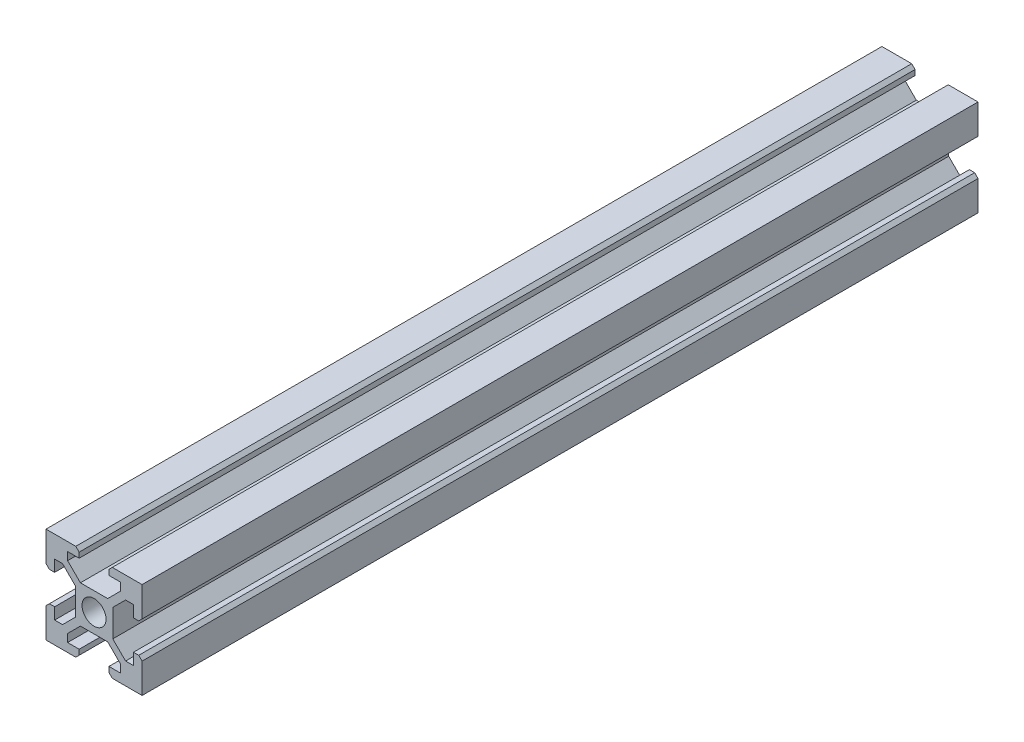
SolidWorks part; units mm, degrees
material "1060 Alloy"
ref_plane "Front Plane" through (0, 0, 0) normal (0, 0, 1) x (1, 0, 0)
ref_plane "Top Plane" through (0, 0, 0) normal (0, 1, 0) x (1, 0, 0)
ref_plane "Right Plane" through (0, 0, 0) normal (1, 0, 0) x (0, 0, -1)
sketch "Sketch1" plane through (0, 0, 0) normal (0, 0, 1) x (1, 0, 0)
  line L0 (3.9, -2.8393) -> (6.5607, -5.5)
  line L1 (-10, 10) -> (10, 10) construction
  line L2 (-10, 10) -> (-10, -10) construction
  line L3 (-10, -10) -> (10, -10) construction
  line L4 (10, 10) -> (10, -10) construction
  line L5 (-10, 10) -> (10, -10) construction
  line L6 (-10, -10) -> (10, 10) construction
  line L7 (-3.9, -3.9) -> (3.9, -3.9) construction
  line L8 (-3.9, -3.9) -> (-3.9, 3.9) construction
  line L9 (-3.9, 3.9) -> (3.9, 3.9) construction
  line L10 (3.9, -3.9) -> (3.9, 3.9) construction
  line L11 (-3.9, -3.9) -> (3.9, 3.9) construction
  line L12 (-3.9, 3.9) -> (3.9, -3.9) construction
  line L13 (-10, 10) -> (-5.5, 10) construction
  line L14 (-10, 10) -> (-10, 5.5) construction
  line L15 (-10, 5.5) -> (-5.5, 5.5) construction
  line L16 (-5.5, 10) -> (-5.5, 5.5) construction
  line L17 (10, 10) -> (5.5, 10) construction
  line L18 (10, 10) -> (10, 5.5) construction
  line L19 (10, 5.5) -> (5.5, 5.5) construction
  line L20 (5.5, 10) -> (5.5, 5.5) construction
  line L21 (-10, -10) -> (-5.5, -10) construction
  line L22 (-10, -10) -> (-10, -5.5) construction
  line L23 (-10, -5.5) -> (-5.5, -5.5) construction
  line L24 (-5.5, -10) -> (-5.5, -5.5) construction
  line L25 (10, -10) -> (5.5, -10) construction
  line L26 (10, -10) -> (10, -5.5) construction
  line L27 (10, -5.5) -> (5.5, -5.5) construction
  line L28 (5.5, -10) -> (5.5, -5.5) construction
  line L29 (2.8393, -3.9) -> (5.5, -6.5607)
  line L30 (-5.5, 6.5607) -> (-2.8393, 3.9)
  line L31 (-6.5607, 5.5) -> (-3.9, 2.8393)
  line L32 (5.5, 6.5607) -> (2.8393, 3.9)
  line L33 (6.5607, 5.5) -> (3.9, 2.8393)
  line L34 (-6.5607, -5.5) -> (-3.9, -2.8393)
  line L35 (-5.5, -6.5607) -> (-2.8393, -3.9)
  line L36 (-2.8393, 3.9) -> (2.8393, 3.9)
  line L37 (-3.9, 2.8393) -> (-3.9, -2.8393)
  line L38 (-2.8393, -3.9) -> (2.8393, -3.9)
  line L39 (3.9, -2.8393) -> (3.9, 2.8393)
  line L40 (5.5, 6.5607) -> (5.5, 8.2007)
  line L41 (5.5, 8.2007) -> (3.1, 8.2007)
  line L42 (3.1, 8.2007) -> (3.1, 9.3)
  line L43 (3.1, 9.3) -> (3.8, 10)
  line L44 (3.8, 10) -> (10, 10)
  line L45 (10, 10) -> (10, 3.8)
  line L46 (10, 3.8) -> (9.3, 3.1)
  line L47 (9.3, 3.1) -> (8.2007, 3.1)
  line L48 (8.2007, 3.1) -> (8.2007, 5.5)
  line L49 (8.2007, 5.5) -> (6.5607, 5.5)
  line L50 (3.1, -8.2007) -> (5.5, -8.2007)
  line L51 (3.1, -9.3) -> (3.1, -8.2007)
  line L52 (3.8, -10) -> (3.1, -9.3)
  line L53 (10, -10) -> (3.8, -10)
  line L54 (10, -3.8) -> (10, -10)
  line L55 (9.3, -3.1) -> (10, -3.8)
  line L56 (8.2007, -3.1) -> (9.3, -3.1)
  line L57 (8.2007, -5.5) -> (8.2007, -3.1)
  line L58 (6.5607, -5.5) -> (8.2007, -5.5)
  line L59 (5.5, -8.2007) -> (5.5, -6.5607)
  line L60 (-8.2007, -3.1) -> (-8.2007, -5.5)
  line L61 (-9.3, -3.1) -> (-8.2007, -3.1)
  line L62 (-10, -3.8) -> (-9.3, -3.1)
  line L63 (-10, -10) -> (-10, -3.8)
  line L64 (-3.8, -10) -> (-10, -10)
  line L65 (-3.1, -9.3) -> (-3.8, -10)
  line L66 (-3.1, -8.2007) -> (-3.1, -9.3)
  line L67 (-5.5, -8.2007) -> (-3.1, -8.2007)
  line L68 (-5.5, -6.5607) -> (-5.5, -8.2007)
  line L69 (-8.2007, -5.5) -> (-6.5607, -5.5)
  line L70 (-3.1, 8.2007) -> (-5.5, 8.2007)
  line L71 (-3.1, 9.3) -> (-3.1, 8.2007)
  line L72 (-3.8, 10) -> (-3.1, 9.3)
  line L73 (-10, 10) -> (-3.8, 10)
  line L74 (-10, 3.8) -> (-10, 10)
  line L75 (-9.3, 3.1) -> (-10, 3.8)
  line L76 (-8.2007, 3.1) -> (-9.3, 3.1)
  line L77 (-8.2007, 5.5) -> (-8.2007, 3.1)
  line L78 (-6.5607, 5.5) -> (-8.2007, 5.5)
  line L79 (-5.5, 8.2007) -> (-5.5, 6.5607)
  circle A0 centre (0, 0) radius 2.5
  point P83 (0, 0)
  dimension "D1" = 5
  dimension "D2" = 20
  dimension "D3" = 7.8
  dimension "D4" = 4.5
  dimension "D5" = 1.5
  dimension "D6" = 0.75
  dimension "D7" = 1.5
  dimension "D8" = 0.75
  dimension "D9" = 1.5
  dimension "D10" = 0.75
  dimension "D11" = 1.5
  dimension "D12" = 0.75
  dimension "D13" = 1.64
  dimension "D14" = 45
  dimension "D15" = 3.1
  dimension "D16" = 6.2
  dimension "D17" = 6.2
  dimension "D18" = 3.1
  dimension "D19" = 4
extrude "Boss-Extrude1" add sketch "Sketch1" along normal mid plane 174 contours L79 L70 L71 L72 L73 L74 L75 L76 L77 L78 L31 L37 L34 L69 L60 L61 L62 L63 L64 L65 L66 L67 L68 L35 L38 L29 L59 L50 L51 L52 L53 L54 L55 L56 L57 L58 L0 L39 L33 L49 L48 L47 L46 L45 L44 L43 L42 L41 L40 L32 L36
